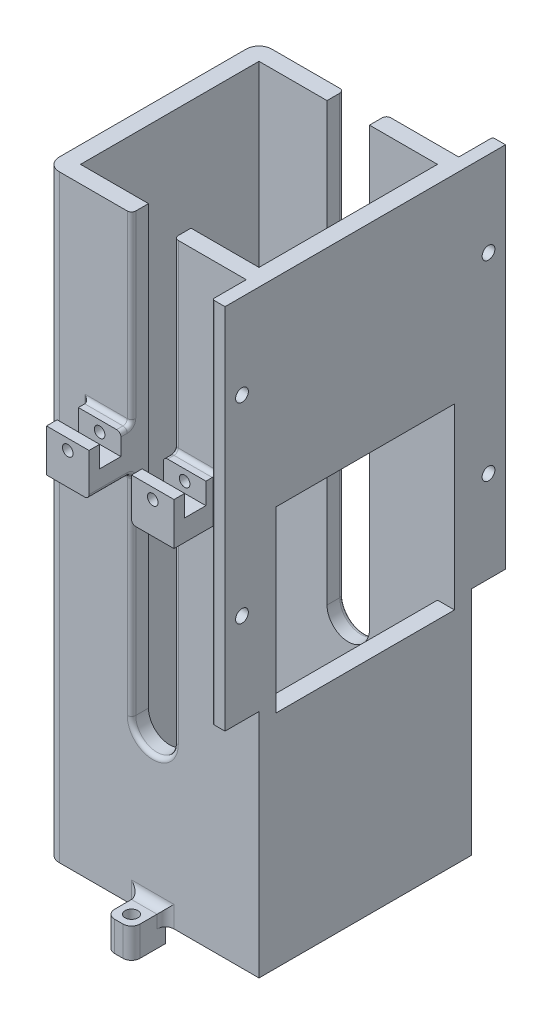
SolidWorks part; units mm, degrees
ref_plane "Front Plane" through (0, 0, 0) normal (0, 0, 1) x (1, 0, 0)
ref_plane "Top Plane" through (0, 0, 0) normal (0, 1, 0) x (1, 0, 0)
ref_plane "Right Plane" through (0, 0, 0) normal (1, 0, 0) x (0, 0, -1)
sketch "Sketch1" plane through (0, 0, 0) normal (0, 1, 0) x (1, 0, 0)
  line L0 (-25, 25) -> (25, 25)
  line L1 (-21, -21) -> (21, -21)
  line L2 (-21, -21) -> (-21, 21)
  line L3 (-21, 21) -> (21, 21)
  line L4 (21, -21) -> (21, 21)
  line L5 (-21, -21) -> (21, 21) construction
  line L6 (-21, 21) -> (21, -21) construction
  line L7 (25, -25) -> (25, 25)
  line L8 (-25, -25) -> (25, -25)
  line L9 (-25, -25) -> (-25, 25)
  point P0 (0, 0)
  dimension "D1" = 42
  dimension "D2" = 42
  dimension "D3" = 4
extrude "Boss-Extrude1" add sketch "Sketch1" along normal blind 140.8
sketch "Sketch3" plane through (0, 0, -25) normal (0, 0, -1) x (-1, 0, 0)
  line L0 (-25, 140.8) -> (25, 140.8) construction
  line L1 (-5, 140.8) -> (5, 140.8)
  line L2 (-5, 140.8) -> (-5, 38)
  line L3 (-5, 33) -> (0, 33) construction
  line L4 (5, 140.8) -> (5, 38)
  line L5 (-25, 0) -> (25, 0) construction
  line L6 (5, 38) -> (5, 33) construction
  line L7 (0, 33) -> (5, 33) construction
  line L8 (-5, 38) -> (-5, 33) construction
  arc A0 (-5, 38) -> (5, 38) centre (0, 38) ccw
  point P6 (0, 140.8)
  dimension "D1" = 10
  dimension "D2" = 33
extrude "Cut-Extrude1" cut sketch "Sketch3" against normal through all
sketch "Sketch5" plane through (0, 0, 25) normal (-1, 0, 0) x (0, 0, 1)
  line L0 (0, 38) -> (0, 140.8) construction
  line L1 (0, 97.5) -> (10, 97.5)
  line L2 (0, 97.5) -> (0, 87.5)
  line L3 (0, 87.5) -> (10, 87.5)
  line L4 (10, 97.5) -> (10, 87.5)
  line L6 (-50, 0) -> (0, 0) construction
  dimension "D1" = 10
  dimension "D2" = 10
  dimension "D3" = 87.5
extrude "Boss-Extrude3" add sketch "Sketch5" along normal blind 15 and the other way blind 15
sketch "Sketch8" plane through (0, 97.5, 0) normal (0, 1, 0) x (1, 0, 0)
  line L0 (15, -35) -> (-15, -35) construction
  line L1 (-5, -25) -> (5, -25)
  line L2 (-5, -25) -> (-5, -35)
  line L3 (-5, -35) -> (5, -35)
  line L4 (5, -25) -> (5, -35)
  line L5 (5, -25) -> (5, -21) construction
extrude "Cut-Extrude4" cut sketch "Sketch8" against normal through all
sketch "Sketch9" plane through (0, 97.5, 0) normal (0, 1, 0) x (1, 0, 0)
  line L0 (-15, -35) -> (-15, -25) construction
  line L1 (-15, -27.5) -> (15, -27.5)
  line L2 (-15, -27.5) -> (-15, -32.5)
  line L3 (-15, -32.5) -> (15, -32.5)
  line L4 (15, -27.5) -> (15, -32.5)
  line L5 (15, -35) -> (15, -25) construction
  line L6 (15, -25) -> (5, -25) construction
  dimension "D1" = 2.5
  dimension "D2" = 5
extrude "Cut-Extrude5" cut sketch "Sketch9" against normal blind 5
sketch "Sketch10" plane through (0, 0, 35) normal (0, 0, 1) x (1, 0, 0)
  line L1 (-15, 95) -> (-5, 95) construction
  line L4 (0, -38.5) -> (0, 38.5) construction
  line L5 (-5, 97.5) -> (-15, 97.5) construction
  line L6 (-15, 97.5) -> (-15, 87.5) construction
  line L7 (-5, 87.5) -> (-5, 97.5) construction
  circle A0 centre (-10, 95) radius 1.25
  circle A1 centre (10, 95) radius 1.25
  dimension "D1" = 2.5
  dimension "D2" = 2.5
extrude "Cut-Extrude6" cut sketch "Sketch10" against normal blind 10
fillet "Fillet5" radius 1 15 edges at (5, 97.5, 26.25) (5, 119.15, 25) (-5, 62.75, 25) (0, 33, 25) (5, 62.75, 25) (-5, 119.15, 25) (-10, 97.5, 25) (-10, 87.5, 25) (15, 92.5, 25) (10, 87.5, 25) (10, 97.5, 25) (-15, 92.5, 25) (5, 87.5, 30) (-5, 87.5, 30) (-5, 97.5, 26.25)
mirror "Mirror7" about plane through (0, 0, 0) normal (0, 0, 1) of "Cut-Extrude6", "Cut-Extrude5", "Cut-Extrude4", "Boss-Extrude3"
fillet "Fillet6" radius 1 15 edges at (5, 62.75, -25) (0, 33, -25) (5, 119.15, -25) (-5, 119.15, -25) (-5, 62.75, -25) (5, 97.5, -26.25) (-5, 97.5, -26.25) (10, 97.5, -25) (15, 92.5, -25) (-10, 97.5, -25) (-15, 92.5, -25) (-10, 87.5, -25) (10, 87.5, -25) (5, 87.5, -30) (-5, 87.5, -30)
sketch "Sketch7" plane through (25, 0, 0) normal (1, 0, 0) x (0, 0, -1)
  line L0 (-25, 0) -> (25, 0) construction
  line L1 (-21, 94) -> (21, 94)
  line L2 (-21, 94) -> (-21, 52)
  line L3 (-21, 52) -> (21, 52)
  line L4 (21, 94) -> (21, 52)
  point P4 (0, 94)
  dimension "D1" = 42
  dimension "D2" = 42
  dimension "D3" = 52
extrude "Cut-Extrude3" cut sketch "Sketch7" against normal up to next
sketch "Sketch12" plane through (0, 0, 0) normal (0, -1, 0) x (1, 0, 0)
  line L0 (25, 25) -> (25, -25) construction
  line L1 (-25, 25) -> (25, 25)
  line L2 (-25, 25) -> (-25, -25)
  line L3 (-25, -25) -> (25, -25)
  line L4 (25, 25) -> (25, -25)
  line L5 (25, -25) -> (-25, -25) construction
extrude "Boss-Extrude5" [suppressed] add sketch "Sketch12" along normal blind 8
sketch "Sketch11" plane through (0, 0, 25) normal (0, 0, 1) x (1, 0, 0)
  line L0 (6, 140.8) -> (25, 140.8) construction
  line L1 (22, 140.8) -> (25, 140.8)
  line L2 (22, 140.8) -> (22, 54.3)
  line L3 (22, 54.3) -> (25, 54.3)
  line L4 (25, 140.8) -> (25, 54.3)
  line L6 (25, 140.8) -> (25, 0) construction
  dimension "D1" = 3
  dimension "D2" = 86.5
extrude "Boss-Extrude4" add sketch "Sketch11" along normal blind 8
sketch "Sketch16" plane through (22, 0, 0) normal (-1, 0, 0) x (0, 0, 1)
  line L0 (29, 140.8) -> (29, 54.3) construction
  line L1 (33, 140.8) -> (25, 140.8) construction
  line L2 (33, 54.3) -> (25, 54.3) construction
  circle A1 centre (29, 120.8) radius 1.5
  circle A3 centre (29, 75.8) radius 1.5
  circle A5 centre (29, 30.8) radius 1.5 [skipped]
  dimension "D1" = 3
  dimension "D4" = 45
  dimension "D2" = 20
  dimension "D3" = 3
extrude "Cut-Extrude11" cut sketch "Sketch16" against normal up to next
mirror "Mirror8" about plane through (0, 0, 0) normal (0, 0, 1) of "Cut-Extrude11", "Boss-Extrude4"
sketch "Sketch13" [suppressed] plane through (0, -8, 0) normal (0, -1, 0) x (1, 0, 0)
  circle A0 centre (0, 0) radius 3.5
  dimension "D1" = 7
extrude "Cut-Extrude7" [suppressed] cut sketch "Sketch13" against normal up to next contours A0
sketch "Sketch14" [suppressed] plane through (0, 0, 0) normal (0, 1, 0) x (1, 0, 0)
  line L1 (-9.5, -8) -> (9.5, -8)
  line L2 (-9.5, -8) -> (-9.5, 8)
  line L3 (-9.5, 8) -> (9.5, 8)
  line L4 (9.5, -8) -> (9.5, 8)
  line L5 (-9.5, -8) -> (9.5, 8) construction
  line L6 (-9.5, 8) -> (9.5, -8) construction
  point P0 (0, 0)
  dimension "D1" = 19
  dimension "D2" = 16
extrude "Cut-Extrude8" [suppressed] cut sketch "Sketch14" against normal blind 5
fillet "Fillet3" radius 3 2 edges at (-25, 70.4, -25) (-25, 70.4, 25)
fillet "Fillet4" radius 0.5 2 edges at (22, 97.55, -33) (22, 97.55, 33)
sketch "Sketch18" plane through (0, 0, 0) normal (0, -1, 0) x (1, 0, 0)
  line L0 (-25, 0) -> (25, 0) construction
  line L1 (-25, -22) -> (-25, 22) construction
  line L2 (25, 25) -> (25, -25) construction
  line L3 (3, 25) -> (3, 33)
  line L4 (-25, 3) -> (-33, 3)
  line L5 (-25, 3) -> (-25, -3)
  line L6 (-25, -3) -> (-33, -3)
  line L7 (-33, 3) -> (-33, -3)
  line L8 (3, 25) -> (-3, 25)
  line L9 (-3, 25) -> (-3, 33)
  line L10 (3, 33) -> (-3, 33)
  line L15 (-3, -25) -> (-3, -33)
  line L16 (-3, -25) -> (3, -25)
  line L17 (3, -25) -> (3, -33)
  line L18 (-3, -33) -> (3, -33)
  line L19 (25, -3) -> (33, -3) [skipped]
  line L20 (25, 3) -> (33, 3) [skipped]
  line L21 (33, -3) -> (33, 3) [skipped]
  line L22 (25, -3) -> (25, 3) [skipped]
  circle A0 centre (-30, 0) radius 1.5
  circle A1 centre (0, 30) radius 1.5
  circle A3 centre (0, -30) radius 1.5
  circle A4 centre (30, 0) radius 1.5 [skipped]
  point P10 (-25, 0)
  point P11 (-29, -3)
  point P35 (0, 0)
  dimension "D3" = 3
  dimension "D1" = 6
  dimension "D2" = 8
  dimension "D4" = 5
  dimension "D5" = 4
extrude "Boss-Extrude6" add sketch "Sketch18" along normal blind 4 and the other way blind 3
fillet "Fillet7" radius 2 15 edges at (3, 1.5, -25) (0, 3, -25) (-3, 1.5, -25) (-25, 1.5, -3) (-25, 1.5, 3) (-25, 3, 0) (0, 3, 25) (3, 1.5, 25) (-3, 1.5, 25) (3, -0.5, 33) (-3, -0.5, 33) (-33, -0.5, 3) (-33, -0.5, -3) (3, -0.5, -33) (-3, -0.5, -33)
